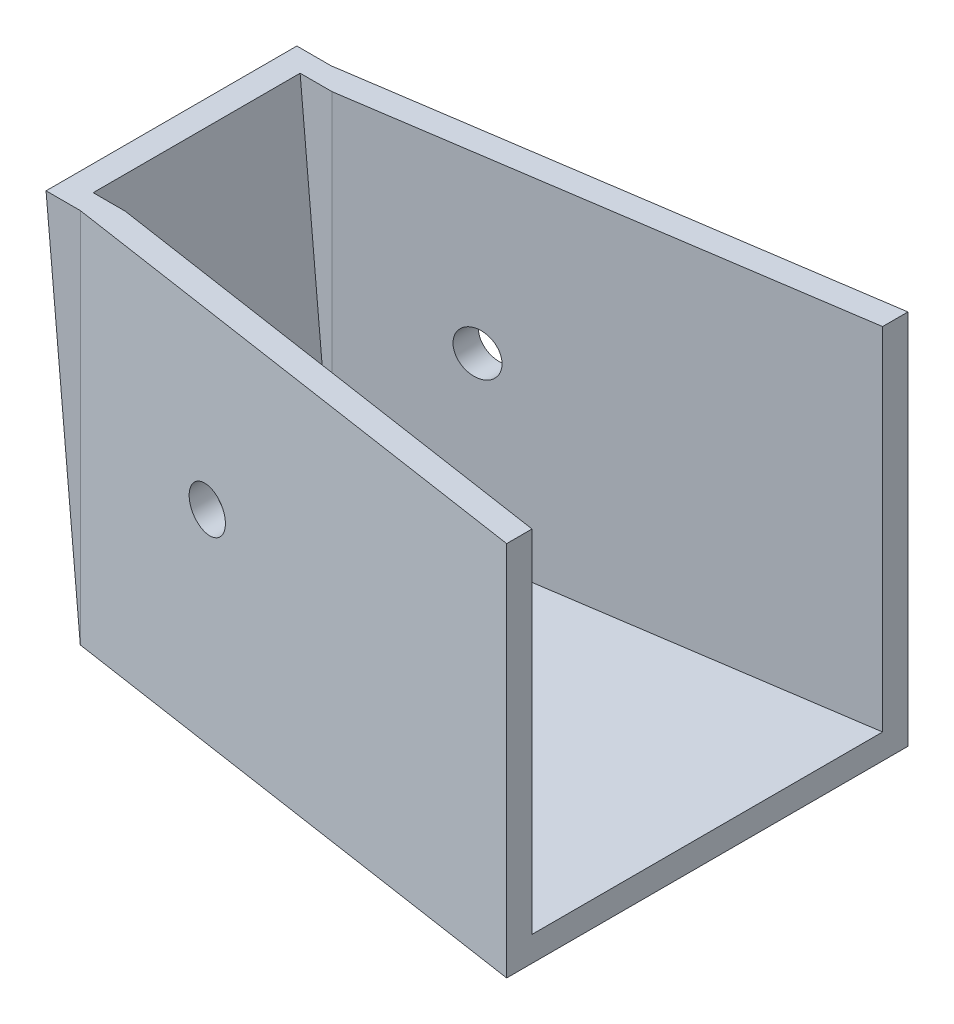
SolidWorks part; units mm, degrees
ref_plane "Front Plane" through (0, 0, 0) normal (0, 0, 1) x (1, 0, 0)
ref_plane "Top Plane" through (0, 0, 0) normal (0, 1, 0) x (1, 0, 0)
ref_plane "Right Plane" through (0, 0, 0) normal (1, 0, 0) x (0, 0, -1)
sketch "Sketch1" plane through (0, 0, 0) normal (0, 1, 0) x (1, 0, 0)
  line L0 (0, -24) -> (0, 24)
  line L1 (0, 0) -> (-60, 0)
  line L2 (-60, -15) -> (-60, 15)
  line L3 (-60, 15) -> (0, 24)
  line L4 (-60, -15) -> (0, -24)
  point P4 (0, 0)
  point P10 (-60, 0)
  dimension "D1" = 60
  dimension "D2" = 30
  dimension "D3" = 48
extrude "Boss-Extrude1" add sketch "Sketch1" along normal blind 3 contours L3 L2 L1 L0 | L2 L4 L0 L1
sketch "Sketch3" plane through (0, 0, 0) normal (0, 0, 1) x (1, 0, 0)
  line L0 (-60, 3) -> (-60, 0) construction
  line L1 (-60, 3) -> (-60, 0) construction
  line L2 (-60, 0) -> (-64.0953, 45)
  line L3 (-64.0953, 45) -> (-60, 45) construction
  line L4 (-60, 45) -> (-60, 0) construction
  line L5 (-61.0829, 45) -> (-56.9876, 0)
  line L6 (-60, 0) -> (0, 0) construction
  line L7 (-60, 0) -> (-56.9876, 0)
  line L8 (-56.9876, 0) -> (-60, 0)
  line L9 (-64.0953, 45) -> (-61.0829, 45)
  dimension "D1" = 45
  dimension "D2" = 5.2
  dimension "D3" = 3
extrude "Boss-Extrude2" add sketch "Sketch3" along normal mid plane 30 contours L9 L2 L7 L5
sketch "Sketch4" plane through (0, 3, 0) normal (0, 1, 0) x (1, 0, 0)
  line L0 (0, 20.9664) -> (-57.2606, 12.3773)
  line L1 (-54.2606, 12.8273) -> (-54.2606, 12.8273)
  line L3 (-54.2606, -12.8273) -> (-54.2606, -12.8273)
  line L4 (-57.2606, -12.3773) -> (0, -20.9664)
  line L6 (-57.2606, -15) -> (-60, -15)
  line L7 (-60, -15) -> (0, -24)
  line L8 (0, -24) -> (0, 24)
  line L9 (0, 24) -> (-60, 15)
  line L10 (-60, 15) -> (-57.2606, 15)
  line L11 (-57.2606, 15) -> (-57.2606, -15)
  line L12 (-57.2606, -15) -> (-60, -15)
  line L13 (-60, -15) -> (0, -24)
  line L14 (0, -24) -> (0, 24)
  line L15 (0, 24) -> (-60, 15)
  line L16 (-60, 15) -> (-57.2606, 15)
  line L17 (-57.2606, 15) -> (-57.2606, -15)
  line L18 (-3, -20.5164) -> (-3, 20.5164) construction
  line L19 (-3, 20.5164) -> (-54.2606, 12.8273) construction
  line L20 (-54.2606, -12.8273) -> (-3, -20.5164) construction
  line L21 (-54.2606, 12.8273) -> (-54.2606, -12.8273) construction
  line M7 (-57.2606, -15) -> (-60, -15)
  line M8 (-60, -15) -> (0, -24)
  line M9 (0, -24) -> (0, 24)
  line M10 (0, 24) -> (-60, 15)
  line M11 (-60, 15) -> (-57.2606, 15)
  line M12 (-57.2606, 15) -> (-57.2606, -15)
  dimension "D1" = 0
  dimension "D2" = 3
extrude "Boss-Extrude3" add sketch "Sketch4" along normal blind 42 contours L0 M9 M10 M11 M12 | L4 M12 M7 M8 M9
sketch "Sketch6" plane through (-57.2606, 0, 0) normal (-1, 0, 0) x (0, 0, 1)
  line L0 (-12.3773, 44.7089) -> (-12.3773, 45)
  line L1 (-12.3773, 45) -> (-12.3773, 3) construction
  line L2 (-12.3773, 45) -> (-12.3773, 44.7089)
  line L3 (-12.3773, 45) -> (-12.3773, 0)
  line L4 (-15, 45) -> (-15, 0)
  line L5 (-15, 0) -> (15, 0)
  line L6 (15, 0) -> (15, 45)
  line L7 (15, 45) -> (-15, 45)
  line L8 (-15, 45) -> (-15, 0)
  line L9 (-15, 0) -> (15, 0)
  line L10 (15, 0) -> (15, 45)
  line L11 (15, 45) -> (12.3773, 45)
  line L12 (12.3773, 45) -> (12.3773, 3) construction
  line L13 (12.3773, 45) -> (12.3773, 0)
  line L14 (-12.3773, 45) -> (-15, 45)
  line M5 (-15, 3) -> (-12.3773, 3)
  line M6 (-12.3773, 3) -> (-12.3773, 45)
  line M8 (-15, 45) -> (-15, 3)
  dimension "D1" = 0
extrude "Boss-Extrude4" add sketch "Sketch6" along normal blind 4 contours L14 M6 M8 M5 | L11 L13 L9 L10
sketch "Sketch7" plane through (0, 0, 15) normal (0, 0, 1) x (1, 0, 0)
  line L0 (-61.2606, 13.8519) -> (-60, 0)
  line L1 (-60, 0) -> (-61.2606, 0)
  line L2 (-61.2606, 13.8519) -> (-61.2606, 0)
  line L5 (-64.0953, 45) -> (-61.2606, 13.8519)
  line L6 (-61.2606, 13.8519) -> (-61.2606, 0)
  line L7 (-61.2606, 0) -> (-60, 0)
  line L8 (-60, 0) -> (-60, 45)
  line L9 (-60, 45) -> (-64.0953, 45)
  line L10 (-64.0953, 45) -> (-61.2606, 13.8519)
  line L11 (-61.2606, 13.8519) -> (-61.2606, 0)
  line L12 (-61.2606, 0) -> (-60, 0)
  line L13 (-60, 0) -> (-60, 45) construction
  line L14 (-60, 45) -> (-64.0953, 45)
  line M8 (-61.2606, 13.8519) -> (-61.2606, 0)
  line M9 (-61.2606, 0) -> (-60, 0)
  dimension "D1" = 0
extrude "Cut-Extrude1" cut sketch "Sketch7" against normal through all contours L0 M8 M9
sketch "Sketch8" plane through (0, 0, 15) normal (0, 0, 1) x (1, 0, 0)
  line L0 (-62.0477, 22.5) -> (-42.13, 24.3127) construction
  line L1 (-60, 0) -> (-64.0953, 45) construction
  circle A0 centre (-42.13, 24.3127) radius 2.55
  dimension "D3" = 5.1
  dimension "D1" = 90
  dimension "D2" = 20
extrude "Cut-Extrude2" cut sketch "Sketch8" against normal mid plane 100
